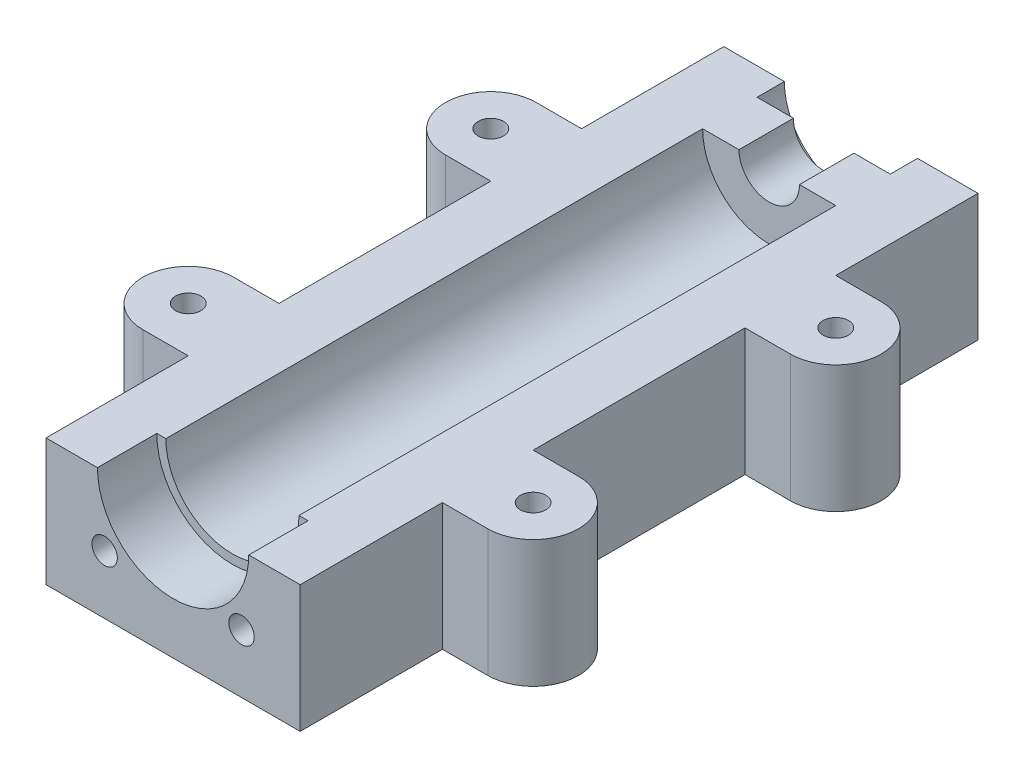
SolidWorks part; units mm, degrees
ref_plane "Спереди" through (0, 0, 0) normal (0, 0, 1) x (1, 0, 0)
ref_plane "Сверху" through (0, 0, 0) normal (0, 1, 0) x (1, 0, 0)
ref_plane "Справа" through (0, 0, 0) normal (1, 0, 0) x (0, 0, -1)
sketch "Эскиз1" plane through (0, 0, 0) normal (0, 1, 0) x (1, 0, 0)
  line L1 (0, 0) -> (21, 0)
  line L2 (0, 0) -> (0, 112)
  line L3 (0, 112) -> (21, 112)
  line L4 (21, 0) -> (21, 112)
  dimension "D1" = 21
  dimension "D2" = 112
revolve "Повернуть1" add sketch "Эскиз1" angle 360 about L2
sketch "Эскиз2" plane through (0, 0, 0) normal (0, 1, 0) x (1, 0, 0)
  line L0 (0, 0) -> (12.5, 0)
  line L1 (-21, 0) -> (21, 0) construction
  line L2 (12.5, 0) -> (12.5, 9.8)
  line L3 (12.5, 9.8) -> (11, 9.8)
  line L4 (11, 9.8) -> (11, 98.5)
  line L5 (11, 98.5) -> (5, 98.5)
  line L6 (5, 98.5) -> (5, 107.5)
  line L7 (5, 107.5) -> (11, 107.5)
  line L8 (11, 107.5) -> (11, 112)
  line L9 (21, 112) -> (-21, 112) construction
  line L10 (11, 112) -> (0, 112)
  line L11 (0, 112) -> (0, 0)
  point P9 (5, 103)
  dimension "D1" = 12.5
  dimension "D2" = 11
  dimension "D3" = 9.8
  dimension "D4" = 9
  dimension "D5" = 88.7
  dimension "D6" = 11
  dimension "D7" = 5
revolve "Вырез-Повернуть1" cut sketch "Эскиз2" angle 360 about L11
sketch "Эскиз3" plane through (0, 0, 0) normal (0, 0, 1) x (1, 0, 0)
  line L1 (-21, 0) -> (21, 0)
  line L2 (-21, 0) -> (-21, 25)
  line L3 (-21, 25) -> (21, 25)
  line L4 (21, 0) -> (21, 25)
  circle A0 centre (0, 0) radius 21 construction
  dimension "D1" = 25
extrude "Вырез-Вытянуть1" cut sketch "Эскиз3" against normal up to surface (112 mm away) up to face at (-11, 0, -112)
ref_plane "Плоскость1" through (0, -21, 0) normal (0, 1, 0) x (1, 0, 0)
sketch "Эскиз4" plane through (0, -21, 0) normal (0, 1, 0) x (1, 0, 0)
  line L5 (-21, 112) -> (21, 112)
  line L6 (-21, 112) -> (-21, 0)
  line L7 (-21, 0) -> (21, 0)
  line L8 (21, 112) -> (21, 0)
extrude "Бобышка-Вытянуть1" add sketch "Эскиз4" along normal up to body separate body
sketch "Эскиз5" plane through (0, -21, 0) normal (0, 1, 0) x (1, 0, 0)
  line L0 (21, 23.5) -> (28.5, 23.5)
  line L1 (21, 112) -> (21, 0) construction
  line L2 (28.5, 38.5) -> (21, 38.5)
  line L3 (21, 38.5) -> (21, 23.5)
  arc A0 (28.5, 23.5) -> (28.5, 38.5) centre (28.5, 31) ccw
  dimension "D1" = 31
  dimension "D2" = 15
  dimension "D3" = 7.5
extrude "Бобышка-Вытянуть2" add sketch "Эскиз5" along normal up to surface (21 mm away) up to face at (12.1, 0, -65.56)
hole_wizard "Сверление под метчик M51" positions "Трехмерный эскиз2" profile "Эскиз7" hole size "M5" standard "ISO" end condition up to next
sketch3d "Трехмерный эскиз2"
  arc A0 (28.5, 0, -38.5) -> (28.5, 0, -23.5) centre (28.5, 0, -31) ccw construction
  point P0 (28.5, 0, -31)
  point P6 (28.5, -7.5, -31)
cosmetic thread "Условное изображение резьбы1" parameters "D2"=5
sketch "Эскиз7" plane through (28.5, 0, -31) normal (1, 0, 0) x (0, 0, 1)
  line L0 (0, 0) -> (0, 21.001)
  line L1 (0, 21.001) -> (2.1, 21.001)
  line L2 (2.1, 21.001) -> (2.1, 0)
  line L5 (2.1, 0) -> (0, 0)
  line L11 (0, -6.35) -> (0, 107.95) construction
  dimension "Диаметр сквозного отверстия" = 4.2
  dimension "Глубина сквозного отверстия" = 21.001
pattern_linear "Линейный массив1" count 2 spacing 50 along (0, 0, -1) of "Бобышка-Вытянуть2", "Сверление под метчик M51"
mirror "Зеркальное отражение1" about plane through (0, 0, 0) normal (1, 0, 0) of "Линейный массив1", "Бобышка-Вытянуть2", "Сверление под метчик M51"
hole_wizard "Сверление под метчик M52" positions "Трехмерный эскиз3" profile "Эскиз8" hole size "M5" standard "ISO"
sketch3d "Трехмерный эскиз3"
  line L0 (0, 0, 0) -> (0, -21, 0) construction
  line L1 (-21, -21, 0) -> (21, -21, 0) construction
  point P0 (11.3137, -11.3137, 0)
  dimension "D1" = 16
  dimension "D2" = 45
cosmetic thread "Условное изображение резьбы2" parameters "D2"=5
sketch "Эскиз8" plane through (11.3137, -11.3137, 0) normal (1, 0, 0) x (0, -1, 0)
  line L0 (0, 0) -> (0, 26.2618)
  line L1 (0, 26.2618) -> (2.1, 25)
  line L2 (2.1, 25) -> (2.1, 0)
  line L5 (2.1, 0) -> (0, 0)
  line L10 (0, 26.2618) -> (-2.1, 25) construction
  line L11 (0, -6.35) -> (0, 107.95) construction
  dimension "Диаметр отверстия" = 4.2
  dimension "Глубина отверстия" = 25
  dimension "Угол заточки сверла" = 118
pattern_circular "Круговой массив1" count 2 every 90 of "Сверление под метчик M52"
ref_plane "Плоскость2" through (0, 0, -56) normal (0, 0, 1) x (1, 0, 0)
mirror "Зеркальное отражение2" about plane through (0, 0, -56) normal (0, 0, 1) of "Сверление под метчик M52", "Круговой массив1"
